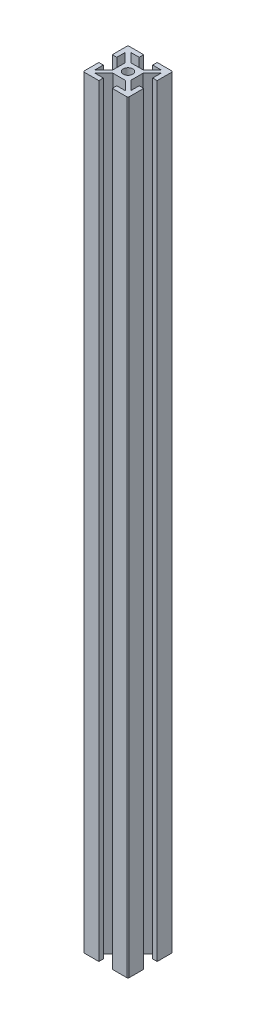
SolidWorks part; units mm, degrees
material "6061 Alloy"
ref_plane "Front Plane" through (0, 0, 0) normal (0, 0, 1) x (1, 0, 0)
ref_plane "Top Plane" through (0, 0, 0) normal (0, 1, 0) x (1, 0, 0)
ref_plane "Right Plane" through (0, 0, 0) normal (1, 0, 0) x (0, 0, -1)
ref_plane "Plane1" through (0, 340, 0) normal (0, 1, 0) x (1, 0, 0)
sketch "Sketch1" plane through (0, 340, 0) normal (0, 1, 0) x (1, 0, 0)
  line L0 (4, 2.7464) -> (8, 6.7464)
  line L1 (8, 6.7464) -> (8, 3)
  line L2 (8, 3) -> (10, 3)
  line L3 (10, 3) -> (10, 9.5)
  line L4 (9.5, 10) -> (3, 10)
  line L5 (3, 10) -> (3, 8)
  line L6 (3, 8) -> (6.8633, 8)
  line L7 (6.8633, 8) -> (2.8633, 4)
  line L8 (2.8633, 4) -> (-2.75, 4)
  line L9 (-2.75, 4) -> (-6.75, 8)
  line L10 (-6.75, 8) -> (-3, 8)
  line L11 (-3, 8) -> (-3, 10)
  line L12 (-3, 10) -> (-9.5, 10)
  line L13 (-10, 9.5) -> (-10, 3)
  line L14 (-10, 3) -> (-8, 3)
  line L15 (-8, 3) -> (-8, 6.75)
  line L16 (-8, 6.75) -> (-4, 2.75)
  line L17 (-4, 2.75) -> (-4, -2.75)
  line L18 (-4, -2.75) -> (-8, -6.75)
  line L19 (-8, -6.75) -> (-8, -3)
  line L20 (-8, -3) -> (-10, -3)
  line L21 (-10, -3) -> (-10, -9.5)
  line L22 (-9.5, -10) -> (-3, -10)
  line L23 (-3, -10) -> (-3, -8)
  line L24 (-3, -8) -> (-6.75, -8)
  line L25 (-6.75, -8) -> (-2.75, -4)
  line L26 (-2.75, -4) -> (2.8685, -4)
  line L27 (2.8685, -4) -> (6.8685, -8)
  line L28 (6.8685, -8) -> (3, -8)
  line L29 (3, -8) -> (3, -10)
  line L30 (3, -10) -> (9.5, -10)
  line L31 (10, -9.5) -> (10, -3)
  line L32 (10, -3) -> (8, -3)
  line L33 (8, -3) -> (8, -6.6652)
  line L34 (8, -6.6652) -> (4, -2.6652)
  line L35 (4, -2.6652) -> (4, 2.7464)
  arc A0 (10, 9.5) -> (9.5, 10) centre (9.5, 9.5) ccw
  arc A1 (-9.5, 10) -> (-10, 9.5) centre (-9.5, 9.5) ccw
  arc A2 (-10, -9.5) -> (-9.5, -10) centre (-9.5, -9.5) ccw
  arc A3 (9.5, -10) -> (10, -9.5) centre (9.5, -9.5) ccw
  circle A4 centre (0, 0) radius 2.1
extrude "Boss-Extrude1" add sketch "Sketch1" against normal blind 340
ref_plane "Plane2" through (0, 0, 0) normal (-1, 0, 0) x (0, 0, 1)
ref_plane "Plane3" through (0, 0, 0) normal (0, 0, 1) x (1, 0, 0)
ref_plane "Plane4" through (0, 170, 0) normal (0, 1, 0) x (1, 0, 0)
